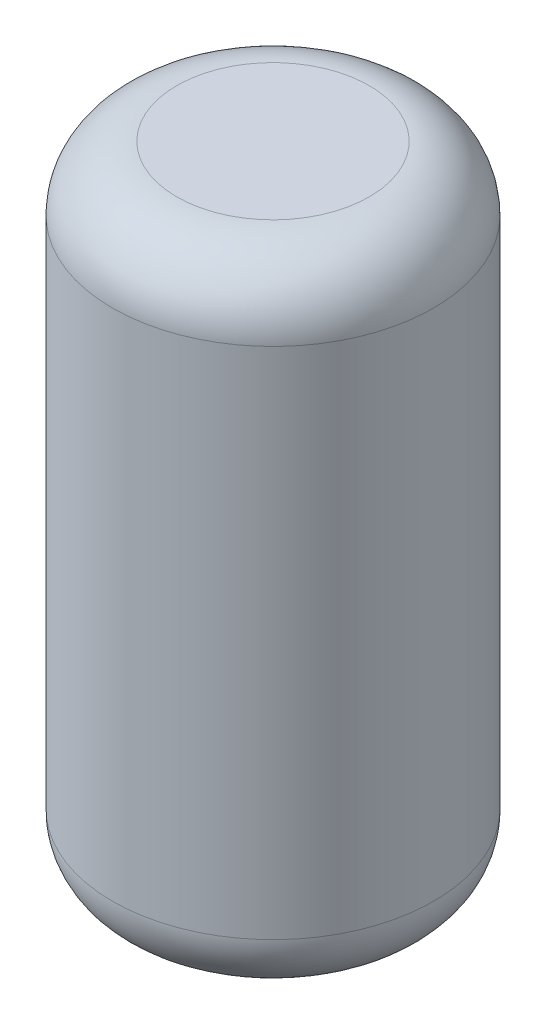
SolidWorks part; units mm, degrees
ref_plane "Alzado" through (0, 0, 0) normal (0, 0, 1) x (1, 0, 0)
ref_plane "Planta" through (0, 0, 0) normal (0, 1, 0) x (1, 0, 0)
ref_plane "Vista lateral" through (0, 0, 0) normal (1, 0, 0) x (0, 0, -1)
sketch "Croquis1" plane through (0, 0, 0) normal (0, 1, 0) x (1, 0, 0)
  circle A0 centre (0, 0) radius 2.5
  dimension "D1" = 5
extrude "Saliente-Extruir2" add sketch "Croquis1" along normal mid plane 10
fillet "Redondeo2" radius 1 2 edges at (0, -5, 2.5) (0, 5, 2.5)
